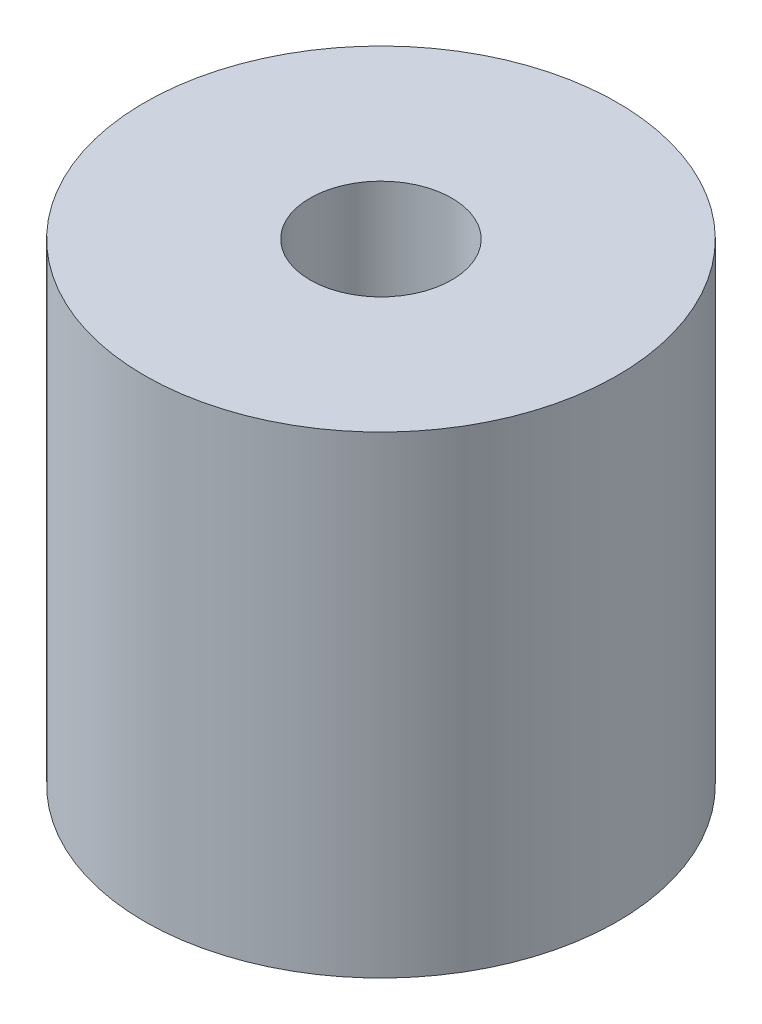
SolidWorks part; units mm, degrees
ref_plane "Front Plane" through (0, 0, 0) normal (0, 0, 1) x (1, 0, 0)
ref_plane "Top Plane" through (0, 0, 0) normal (0, 1, 0) x (1, 0, 0)
ref_plane "Right Plane" through (0, 0, 0) normal (1, 0, 0) x (0, 0, -1)
sketch "Sketch1" plane through (0, 0, 0) normal (0, 1, 0) x (1, 0, 0)
  circle A0 centre (0, 0) radius 2.5
  dimension "D1" = 5
extrude "Boss-Extrude1" add sketch "Sketch1" along normal blind 5
sketch "Sketch2" plane through (0, 5, 0) normal (0, 1, 0) x (1, 0, 0)
  circle A0 centre (0, 0) radius 0.75
  dimension "D1" = 1.5
extrude "Cut-Extrude1" cut sketch "Sketch2" against normal blind 5
